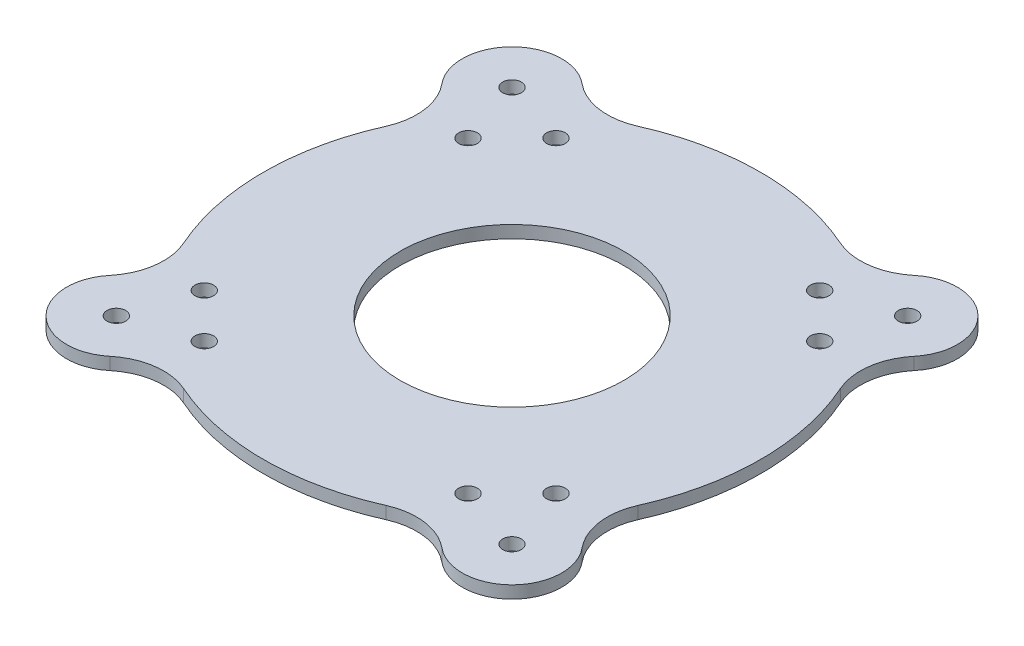
SolidWorks part; units mm, degrees
material "Thornel Mat VMA"
ref_plane "前视基准面" through (0, 0, 0) normal (0, 0, 1) x (1, 0, 0)
ref_plane "上视基准面" through (0, 0, 0) normal (0, 1, 0) x (1, 0, 0)
ref_plane "右视基准面" through (0, 0, 0) normal (1, 0, 0) x (0, 0, -1)
sketch "草图1" plane through (0, 0, 0) normal (0, 1, 0) x (1, 0, 0)
  line L6 (-30, 0) -> (30, 0) construction
  circle A4 centre (0, 0) radius 40
  circle A5 centre (0, 0) radius 18
  dimension "D7" = 80
  dimension "D8" = 36
  dimension "D1" = 60
  dimension "D2" = 0
extrude "凸台-拉伸1" add sketch "草图1" along normal blind 2
sketch "草图4" plane through (0, 0, 0) normal (0, -1, 0) x (1, 0, 0)
  line L0 (0, 0) -> (35223.4625, 35223.4625) construction
  line L1 (-1000, 0) -> (49000, 0) construction
  line L2 (24.7487, 24.7487) -> (31.8198, 31.8198) construction
  line L3 (19.0919, 30.4056) -> (26.163, 37.4767)
  line L4 (30.4056, 19.0919) -> (37.4767, 26.163)
  line L5 (19.0919, -30.4056) -> (26.163, -37.4767)
  line L6 (30.4056, -19.0919) -> (37.4767, -26.163)
  line L7 (24.7487, -24.7487) -> (31.8198, -31.8198) construction
  line L8 (-30.4056, -19.0919) -> (-37.4767, -26.163)
  line L9 (-19.0919, -30.4056) -> (-26.163, -37.4767)
  line L10 (-24.7487, -24.7487) -> (-31.8198, -31.8198) construction
  line L11 (-19.0919, 30.4056) -> (-26.163, 37.4767)
  line L12 (-30.4056, 19.0919) -> (-37.4767, 26.163)
  line L13 (-24.7487, 24.7487) -> (-31.8198, 31.8198) construction
  arc A0 (19.0919, 30.4056) -> (30.4056, 19.0919) centre (24.7487, 24.7487) ccw
  arc A1 (37.4767, 26.163) -> (26.163, 37.4767) centre (31.8198, 31.8198) ccw
  circle A2 centre (0, 0) radius 40 construction
  arc A3 (30.4056, -19.0919) -> (19.0919, -30.4056) centre (24.7487, -24.7487) ccw
  arc A4 (26.163, -37.4767) -> (37.4767, -26.163) centre (31.8198, -31.8198) ccw
  arc A5 (-19.0919, -30.4056) -> (-30.4056, -19.0919) centre (-24.7487, -24.7487) ccw
  arc A6 (-37.4767, -26.163) -> (-26.163, -37.4767) centre (-31.8198, -31.8198) ccw
  arc A7 (-30.4056, 19.0919) -> (-19.0919, 30.4056) centre (-24.7487, 24.7487) ccw
  arc A8 (-26.163, 37.4767) -> (-37.4767, 26.163) centre (-31.8198, 31.8198) ccw
  point P8 (28.2843, 28.2843)
  point P21 (28.2843, -28.2843)
  point P28 (-28.2843, -28.2843)
  point P35 (-28.2843, 28.2843)
  point P40 (0, 0)
  dimension "D4" = 8
  dimension "D1" = 45
  dimension "D2" = 35
  dimension "D3" = 45
  dimension "D5" = 4
extrude "凸台-拉伸2" add sketch "草图4" against normal blind 2
fillet "圆角1" radius 10 8 edges at (-22.056, 1, -33.3697) (-33.3697, 1, -22.056) (-33.3697, 1, 22.056) (-22.056, 1, 33.3697) (22.056, 1, 33.3697) (33.3697, 1, 22.056) (33.3697, 1, -22.056) (22.056, 1, -33.3697)
sketch "草图2" plane through (0, 2, 0) normal (0, 1, 0) x (1, 0, 0)
  line L0 (-11.4642, -11.4642) -> (21203.9468, 21203.9468) construction
  line L1 (-21.6254, -27.8721) -> (-35287.1002, 35237.6027) construction
  line L2 (-1000, 0) -> (49000, 0) construction
  circle A2 centre (-21.2132, -28.2843) radius 1.5
  circle A9 centre (-31.8198, -31.8198) radius 1.5
  circle A17 centre (-28.2843, -21.2132) radius 1.5
  arc A33 (-37.9793, -26.7149) -> (-26.7149, -37.9793) centre (-31.8198, -31.8198) ccw construction
  circle A34 centre (-31.8198, 31.8198) radius 1.5
  circle A35 centre (-21.2132, 28.2843) radius 1.5
  circle A36 centre (-28.2843, 21.2132) radius 1.5
  circle A37 centre (31.8198, 31.8198) radius 1.5
  circle A38 centre (28.2843, 21.2132) radius 1.5
  circle A39 centre (21.2132, 28.2843) radius 1.5
  circle A40 centre (31.8198, -31.8198) radius 1.5
  circle A41 centre (21.2132, -28.2843) radius 1.5
  circle A42 centre (28.2843, -21.2132) radius 1.5
  point P21 (0, 0)
  point P38 (0, 0)
  point P42 (0, 0)
  dimension "D1" = 3
  dimension "D3" = 0
  dimension "D4" = 45
  dimension "D6" = 3
  dimension "D7" = 5
  dimension "D5" = 0
  dimension "D8" = 90
  dimension "D9" = 10
extrude "切除-拉伸1" cut sketch "草图2" against normal through all
